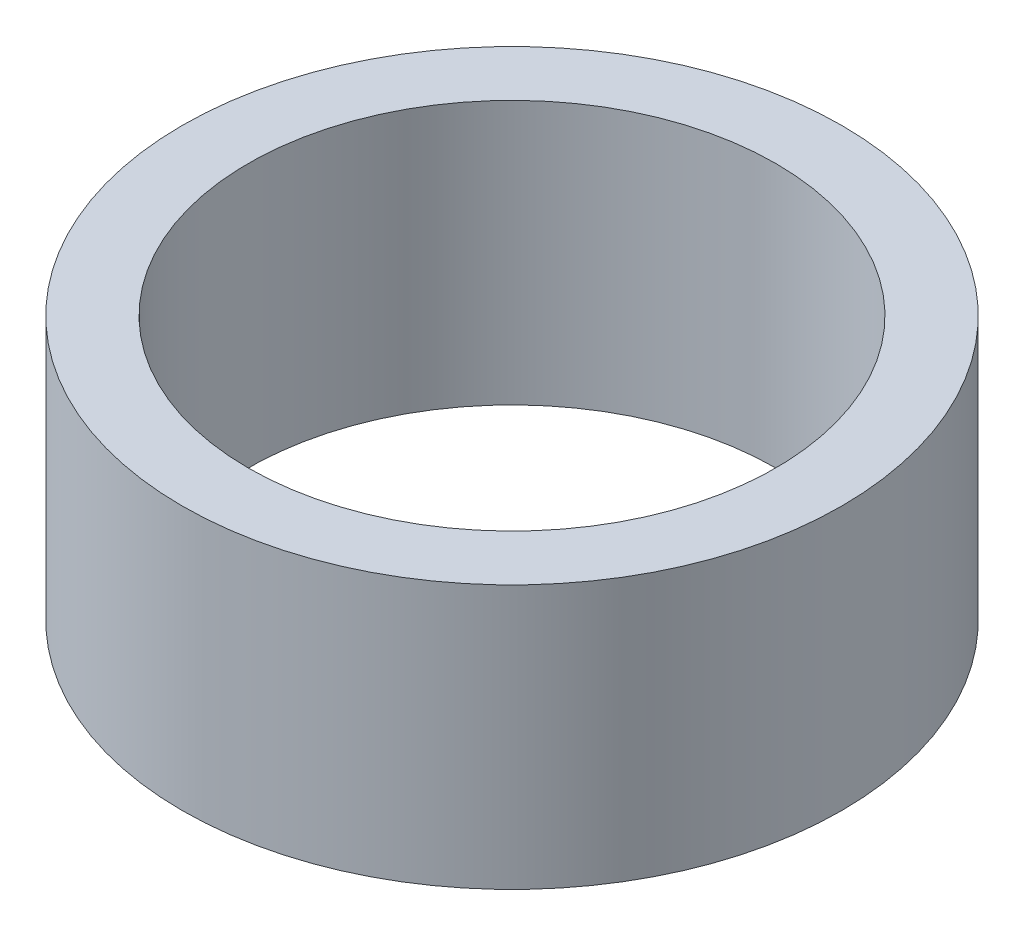
SolidWorks part; units mm, degrees
ref_plane "Front Plane" through (0, 0, 0) normal (0, 0, 1) x (1, 0, 0)
ref_plane "Top Plane" through (0, 0, 0) normal (0, 1, 0) x (1, 0, 0)
ref_plane "Right Plane" through (0, 0, 0) normal (1, 0, 0) x (0, 0, -1)
sketch "Sketch1" plane through (0, 0, 0) normal (0, 1, 0) x (1, 0, 0)
  circle A0 centre (0, 0) radius 63.5
  dimension "D1" = 127
extrude "Boss-Extrude1" add sketch "Sketch1" along normal blind 50.8
sketch "Sketch2" plane through (0, 50.8, 0) normal (0, 1, 0) x (1, 0, 0)
  circle A0 centre (0, 0) radius 50.8
  dimension "D1" = 101.6
extrude "Cut-Extrude1" cut sketch "Sketch2" against normal through all
